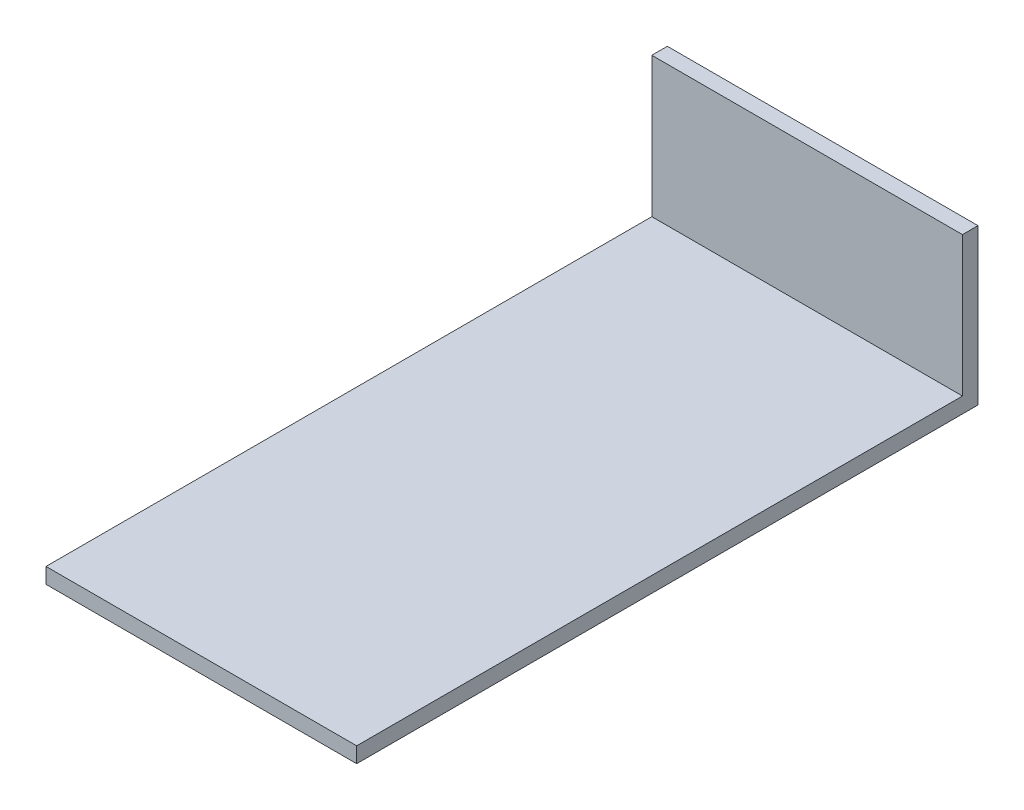
SolidWorks part; units mm, degrees
material "BUTYL"
ref_plane "Front" through (0, 0, 0) normal (0, 0, 1) x (1, 0, 0)
ref_plane "Top" through (0, 0, 0) normal (0, 1, 0) x (1, 0, 0)
ref_plane "Right" through (0, 0, 0) normal (1, 0, 0) x (0, 0, -1)
sketch "Sketch1" plane through (0, 0, 0) normal (0, 0, 1) x (1, 0, 0)
  line L1 (-12.7, -6.35) -> (12.7, -6.35)
  line L2 (-12.7, -6.35) -> (-12.7, 6.35)
  line L3 (-12.7, 6.35) -> (12.7, 6.35)
  line L4 (12.7, -6.35) -> (12.7, 6.35)
  line L5 (-12.7, -6.35) -> (12.7, 6.35) construction
  line L6 (-12.7, 6.35) -> (12.7, -6.35) construction
  point P0 (0, 0)
  dimension "D1" = 25.4
  dimension "D2" = 12.7
extrude "Boss-Extrude1" add sketch "Sketch1" along normal blind 50.8
shell "Shell1" thickness 1.27
